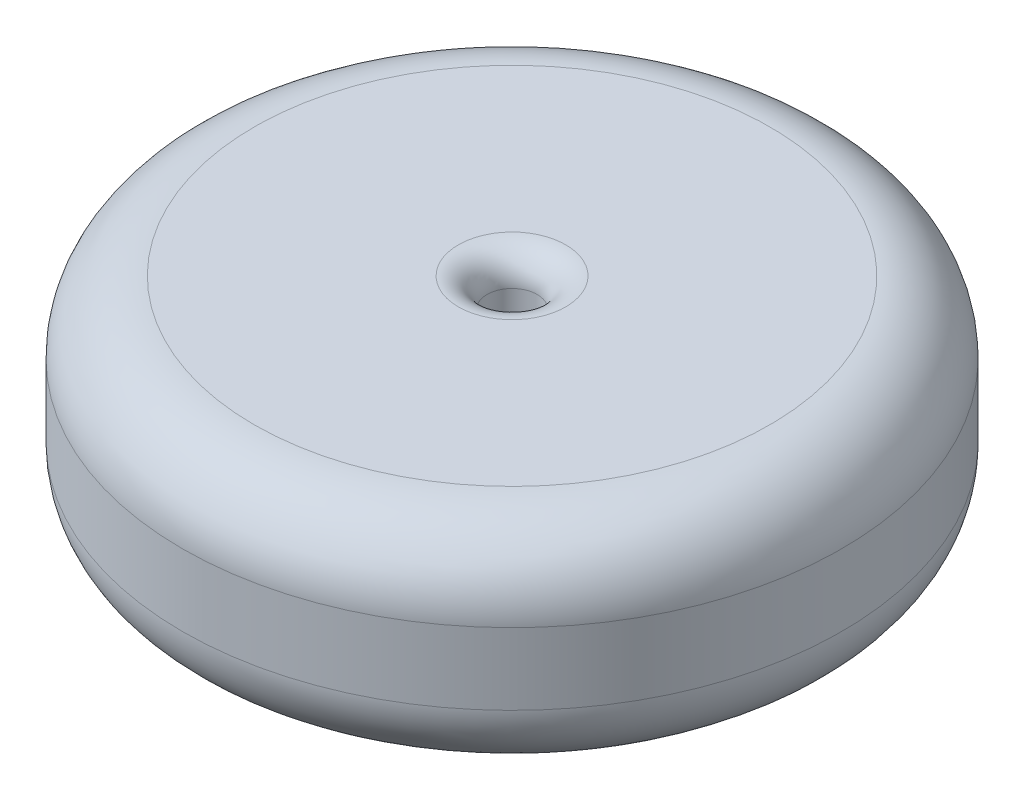
SolidWorks part; units mm, degrees
ref_plane "Front Plane" through (0, 0, 0) normal (0, 0, 1) x (1, 0, 0)
ref_plane "Top Plane" through (0, 0, 0) normal (0, 1, 0) x (1, 0, 0)
ref_plane "Right Plane" through (0, 0, 0) normal (1, 0, 0) x (0, 0, -1)
sketch "Sketch1" plane through (0, 0, 0) normal (0, 1, 0) x (1, 0, 0)
  circle A0 centre (0, 0) radius 23
  circle A1 centre (0, 0) radius 1.75
  dimension "D1" = 46
  dimension "D2" = 3.5
extrude "Boss-Extrude1" add sketch "Sketch1" along normal blind 15
fillet "Fillet1" radius 2 2 edges at (0, 0, 1.75) (0, 15, 1.75)
fillet "Fillet2" radius 5 2 edges at (0, 0, 23) (0, 15, 23)
